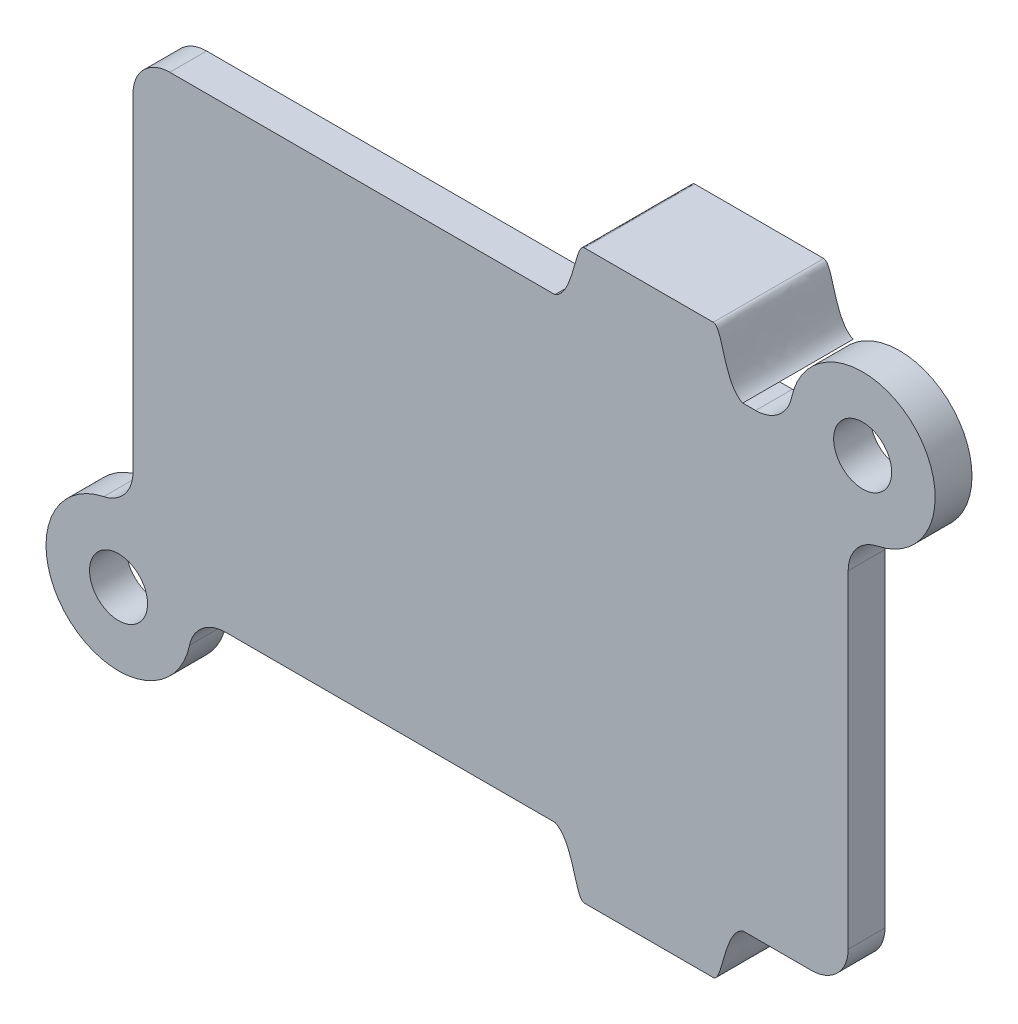
SolidWorks part; units mm, degrees
ref_plane "Front Plane" through (0, 0, 0) normal (0, 0, 1) x (1, 0, 0)
ref_plane "Top Plane" through (0, 0, 0) normal (0, 1, 0) x (1, 0, 0)
ref_plane "Right Plane" through (0, 0, 0) normal (1, 0, 0) x (0, 0, -1)
sketch "Sketch1" plane through (0, 0, 0) normal (0, 0, 1) x (1, 0, 0)
  line L0 (38.3786, 3.1545) -> (38.3786, -15.0065) construction
  line L2 (40.9186, -15.0065) -> (40.9186, 3.1545) construction
  line L4 (-2.0346, -21.693) -> (38.3786, -21.693) construction
  line L5 (40.9186, -19.153) -> (40.9186, -15.0065) construction
  line L7 (38.3786, -15.0065) -> (38.3786, -17.883) construction
  line L8 (37.1086, -19.153) -> (-4.6109, -19.153) construction
  line L9 (-5.8809, -17.883) -> (-5.8809, -14.6382) construction
  line L11 (-8.4209, -14.6382) -> (-8.4209, -15.3067) construction
  line L12 (-5.8809, -14.6382) -> (-5.8809, 2.7862) construction
  line L14 (-8.4209, 2.7862) -> (-8.4209, -14.6382) construction
  line L16 (34.5322, 9.8411) -> (-5.8809, 9.8411) construction
  line L17 (-8.4209, 7.3011) -> (-8.4209, 2.7862) construction
  line L19 (-5.8809, 2.7862) -> (-5.8809, 6.0311) construction
  line L20 (-4.6109, 7.3011) -> (37.1086, 7.3011) construction
  line L21 (38.3786, 6.0311) -> (38.3786, 3.1545) construction
  line L23 (40.9186, 3.1545) -> (40.9186, 3.4547) construction
  line L24 (38.3786, 3.1545) -> (38.3786, -15.0065)
  line L26 (40.9186, -15.0065) -> (40.9186, 3.1545)
  line L28 (-2.0346, -21.693) -> (38.3786, -21.693)
  line L29 (40.9186, -19.153) -> (40.9186, -15.0065)
  line L31 (38.3786, -15.0065) -> (38.3786, -17.883)
  line L32 (37.1086, -19.153) -> (-4.6109, -19.153)
  line L33 (-5.8809, -17.883) -> (-5.8809, -14.6382)
  line L35 (-8.4209, -14.6382) -> (-8.4209, -15.3067)
  line L36 (-5.8809, -14.6382) -> (-5.8809, 2.7862)
  line L38 (-8.4209, 2.7862) -> (-8.4209, -14.6382)
  line L40 (34.5322, 9.8411) -> (-5.8809, 9.8411)
  line L41 (-8.4209, 7.3011) -> (-8.4209, 2.7862)
  line L43 (-5.8809, 2.7862) -> (-5.8809, 6.0311)
  line L44 (-4.6109, 7.3011) -> (37.1086, 7.3011)
  line L45 (38.3786, 6.0311) -> (38.3786, 3.1545)
  line L47 (40.9186, 3.1545) -> (40.9186, 3.4547)
  arc A0 (-10.4418, -17.7931) -> (-4.521, -23.7139) centre (-9.4191, -22.6913) ccw construction
  arc A1 (-2.0346, -21.693) -> (-4.521, -23.7139) centre (-2.0346, -24.233) ccw construction
  arc A2 (38.3786, -21.693) -> (40.9186, -19.153) centre (38.3786, -19.153) ccw construction
  arc A3 (37.1086, -19.153) -> (38.3786, -17.883) centre (37.1086, -17.883) ccw construction
  arc A4 (-5.8809, -17.883) -> (-4.6109, -19.153) centre (-4.6109, -17.883) ccw construction
  arc A5 (-10.4418, -17.7931) -> (-8.4209, -15.3067) centre (-10.9609, -15.3067) ccw construction
  arc A6 (42.9395, 5.9411) -> (37.0186, 11.8619) centre (41.9168, 10.8393) ccw construction
  arc A7 (34.5322, 9.8411) -> (37.0186, 11.8619) centre (34.5322, 12.3811) ccw construction
  arc A8 (-5.8809, 9.8411) -> (-8.4209, 7.3011) centre (-5.8809, 7.3011) ccw construction
  arc A9 (-4.6109, 7.3011) -> (-5.8809, 6.0311) centre (-4.6109, 6.0311) ccw construction
  arc A10 (38.3786, 6.0311) -> (37.1086, 7.3011) centre (37.1086, 6.0311) ccw construction
  arc A11 (42.9395, 5.9411) -> (40.9186, 3.4547) centre (43.4586, 3.4547) ccw construction
  arc A12 (-10.4418, -17.7931) -> (-4.521, -23.7139) centre (-9.4191, -22.6913) ccw
  arc A13 (-2.0346, -21.693) -> (-4.521, -23.7139) centre (-2.0346, -24.233) ccw
  arc A14 (38.3786, -21.693) -> (40.9186, -19.153) centre (38.3786, -19.153) ccw
  arc A15 (37.1086, -19.153) -> (38.3786, -17.883) centre (37.1086, -17.883) ccw
  arc A16 (-5.8809, -17.883) -> (-4.6109, -19.153) centre (-4.6109, -17.883) ccw
  arc A17 (-10.4418, -17.7931) -> (-8.4209, -15.3067) centre (-10.9609, -15.3067) ccw
  arc A18 (42.9395, 5.9411) -> (37.0186, 11.8619) centre (41.9168, 10.8393) ccw
  arc A19 (34.5322, 9.8411) -> (37.0186, 11.8619) centre (34.5322, 12.3811) ccw
  arc A20 (-5.8809, 9.8411) -> (-8.4209, 7.3011) centre (-5.8809, 7.3011) ccw
  arc A21 (-4.6109, 7.3011) -> (-5.8809, 6.0311) centre (-4.6109, 6.0311) ccw
  arc A22 (38.3786, 6.0311) -> (37.1086, 7.3011) centre (37.1086, 6.0311) ccw
  arc A23 (42.9395, 5.9411) -> (40.9186, 3.4547) centre (43.4586, 3.4547) ccw
  circle A26 centre (41.9168, 10.8393) radius 2
  circle A27 centre (-9.4191, -22.6913) radius 2
  dimension "D1" = 4
extrude "Boss-Extrude1" add sketch "Sketch1" along normal blind 2.54 contours L45 A22 L44 A21 L43 L36 L33 A16 L32 A15 L31 L24 | A23 A18 A19 L40 A20 L41 L38 L35 A17 A12 A13 L28 A14 L29 L26 L47 A27 A26 A22 L45 L24 L31 A15 L32 A16 L33 L36 L43 A21 L44
sketch "Sketch2" plane through (0, 0, 2.54) normal (0, 0, 1) x (1, 0, 0)
  line L0 (34.5322, 9.8411) -> (-5.8809, 9.8411) construction
  line L1 (22.723, 9.8411) -> (31.613, 9.8411)
  line L2 (22.723, 9.8411) -> (22.723, 13.6511)
  line L3 (22.723, 13.6511) -> (31.613, 13.6511)
  line L4 (31.613, 9.8411) -> (31.613, 13.6511)
  line L5 (18.172, -21.693) -> (18.172, 9.8411) construction
  line L6 (-2.0346, -21.693) -> (38.3786, -21.693) construction
  line L7 (18.172, -5.926) -> (44.4541, -5.926) construction
  line L8 (22.723, -25.503) -> (31.613, -25.503)
  line L9 (31.613, -21.693) -> (31.613, -25.503)
  line L10 (22.723, -21.693) -> (31.613, -21.693)
  line L11 (22.723, -21.693) -> (22.723, -25.503)
  line L12 (27.168, 13.6511) -> (27.168, 9.8411) construction
  line L13 (52.2458, 13.6511) -> (50.664, 13.6511) construction
  line L14 (31.613, 9.8411) -> (33.6455, 9.8411)
  line L15 (22.723, 9.8411) -> (20.6906, 9.8411)
  line L16 (31.613, -21.693) -> (33.6455, -21.693)
  line L17 (22.723, -21.693) -> (20.6906, -21.693)
  spline S0 degree 3 poles (31.613, 13.6511) (32.2851, 13.6511) (32.3165, 10.4274) (33.6455, 9.8411) knots 0 0 0 0 1 1 1 1
  spline S1 degree 3 poles (22.723, 13.6511) (22.0509, 13.6511) (22.0195, 10.4274) (20.6906, 9.8411) knots 0 0 0 0 1 1 1 1
  spline S2 degree 3 poles (31.613, -25.503) (32.2851, -25.503) (32.3165, -22.2794) (33.6455, -21.693) knots 0 0 0 0 1 1 1 1
  spline S3 degree 3 poles (22.723, -25.503) (22.0509, -25.503) (22.0195, -22.2794) (20.6906, -21.693) knots 0 0 0 0 1 1 1 1
  point P22 (33.6455, 9.8411)
  line M16 (34.5322, 9.8411) -> (-5.8809, 9.8411)
  line M22 (-2.0346, -21.693) -> (38.3786, -21.693)
  dimension "D1" = 3.81
  dimension "D2" = 8.89
  dimension "D3" = 4.551
extrude "Boss-Extrude2" add sketch "Sketch2" against normal blind 7.62 contours L9 S2 M22 | S3 L11 M22 | L11 L8 L9 M22 | L2 S1 M16 | L4 L3 L2 M16 | S0 L4 M16
